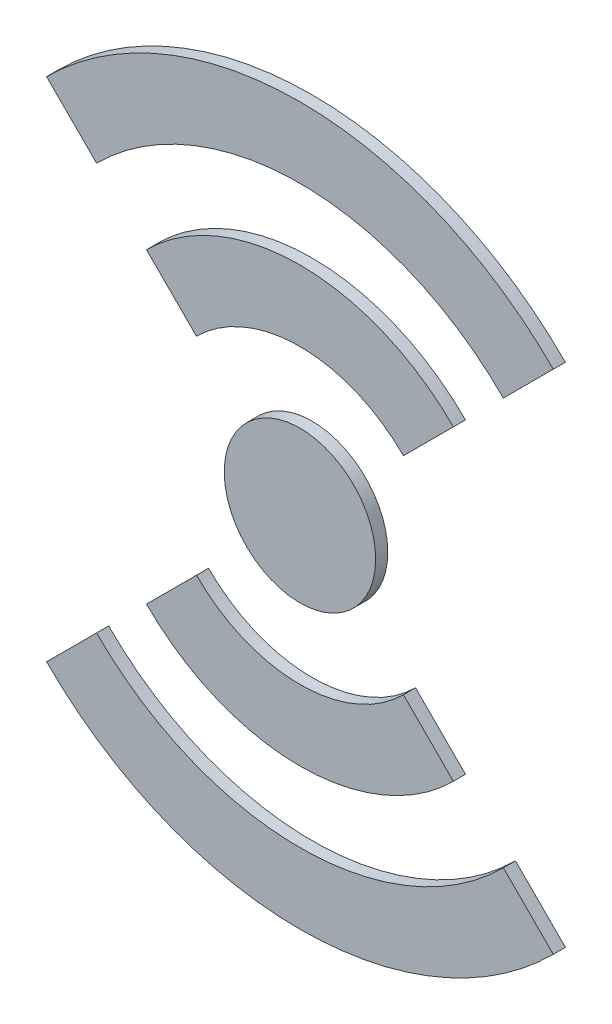
SolidWorks part; units mm, degrees
ref_plane "Přední rovina" through (0, 0, 0) normal (0, 0, 1) x (1, 0, 0)
ref_plane "Horní rovina" through (0, 0, 0) normal (0, 1, 0) x (1, 0, 0)
ref_plane "Pravá rovina" through (0, 0, 0) normal (1, 0, 0) x (0, 0, -1)
sketch "Skica1" plane through (0, 0, 0) normal (0, 0, 1) x (1, 0, 0)
  line L0 (0, 0) -> (36.4973, 36.4973)
  line L1 (36.4973, 36.4973) -> (-34.1146, -34.1146)
  line L2 (0, 0) -> (-30.9812, 30.9812)
  line L3 (-30.9812, 30.9812) -> (39.2609, -39.2609)
  circle A0 centre (0, 0) radius 7.5
  circle A1 centre (0, 0) radius 14.5
  circle A2 centre (0, 0) radius 21.5
  circle A3 centre (0, 0) radius 28.5
  circle A4 centre (0, 0) radius 35.5
  dimension "D1" = 15
  dimension "D2" = 7
  dimension "D3" = 7
  dimension "D4" = 7
  dimension "D5" = 7
extrude "Přidat vysunutím1" add sketch "Skica1" along normal blind 1.2
